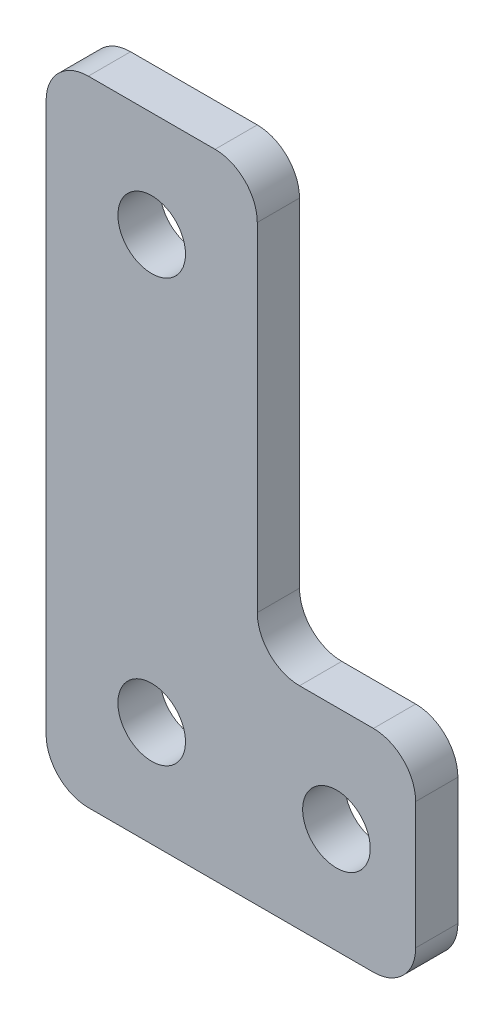
SolidWorks part; units mm, degrees
material "1060 合金"
ref_plane "正面" through (0, 0, 0) normal (0, 0, 1) x (1, 0, 0)
ref_plane "平面" through (0, 0, 0) normal (0, 1, 0) x (1, 0, 0)
ref_plane "右側面" through (0, 0, 0) normal (1, 0, 0) x (0, 0, -1)
sketch "ｽｹｯﾁ1" plane through (0, 0, 0) normal (0, 0, 1) x (1, 0, 0)
  line L0 (5, 30) -> (5, 0) construction
  line L1 (0, 0) -> (10, 0)
  line L2 (0, 0) -> (0, 30)
  line L3 (0, 30) -> (10, 30)
  line L5 (0, 15) -> (10, 15) construction
  line L6 (17.5, 5) -> (5, 5) construction
  line L7 (10, 10) -> (17.5, 10)
  line L9 (10, 0) -> (17.5, 0)
  line L10 (17.5, 10) -> (17.5, 0)
  line L11 (10, 10) -> (10, 30)
  circle A0 centre (5, 25) radius 1.6
  circle A1 centre (5, 5) radius 1.6
  circle A2 centre (13.75, 5) radius 1.6
  dimension "D3" = 3.2
  dimension "D4" = 10
  dimension "D6" = 3.75
  dimension "D1" = 10
  dimension "D2" = 30
  dimension "D5" = 7.5
  dimension "D7" = 10
extrude "ﾎﾞｽ - 押し出し1" add sketch "ｽｹｯﾁ1" along normal blind 2
fillet "ﾌｨﾚｯﾄ2" radius 2 6 edges at (0, 0, 1) (0, 30, 1) (17.5, 0, 1) (17.5, 10, 1) (10, 10, 1) (10, 30, 1)
